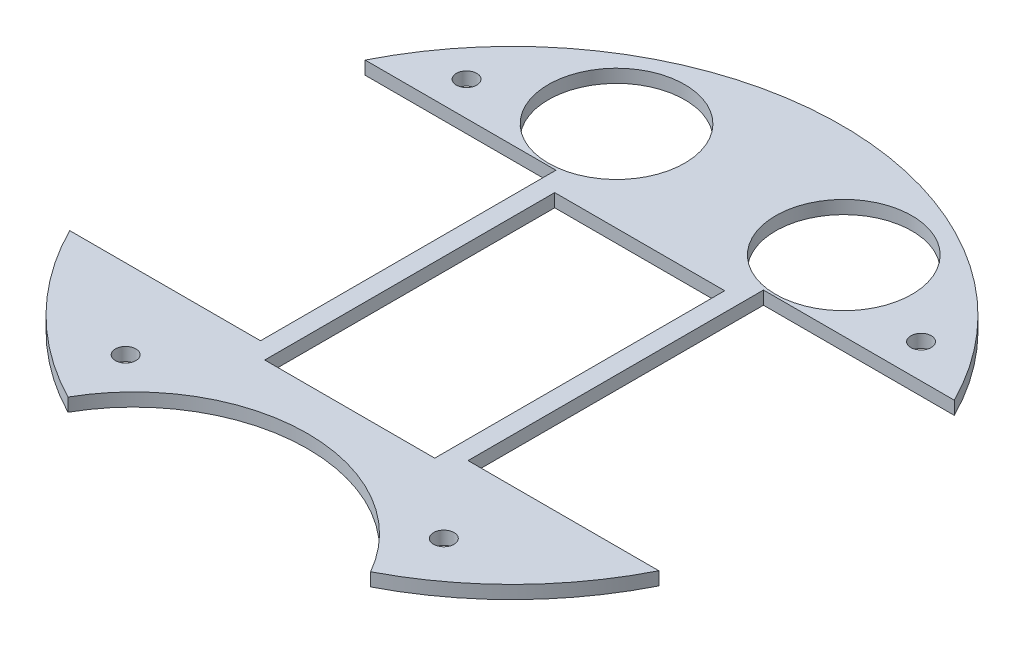
SolidWorks part; units mm, degrees
material "Acrylic (Medium-high impact)"
ref_plane "Front Plane" through (0, 0, 0) normal (0, 0, 1) x (1, 0, 0)
ref_plane "Top Plane" through (0, 0, 0) normal (0, 1, 0) x (1, 0, 0)
ref_plane "Right Plane" through (0, 0, 0) normal (1, 0, 0) x (0, 0, -1)
sketch "Sketch1" plane through (0, 0, 0) normal (0, 1, 0) x (1, 0, 0)
  line L0 (0, -83.2398) -> (-33.2911, -64.4046) construction
  line L1 (0, -83.2398) -> (0, 0) construction
  arc A0 (33.2911, -64.4046) -> (-33.2911, -64.4046) centre (0, 0) ccw
  arc A1 (33.2911, -64.4046) -> (-33.2911, -64.4046) centre (0, -83.2398) ccw
  dimension "D1" = 145
  dimension "D2" = 76.5
  dimension "D3" = 60.5
extrude "Boss-Extrude1" add sketch "Sketch1" along normal blind 2.9
sketch "solenoid placement" plane through (0, 2.9, 0) normal (0, 1, 0) x (1, 0, 0)
  line L0 (0, 0) -> (0, -36) construction
  line L1 (0, -36) -> (0, -44.9898) construction
  line L2 (-19, -36) -> (19, -36) construction
  line L3 (-19, -36) -> (-19, 28.4) construction
  line L4 (-19, 28.4) -> (19, 28.4) construction
  line L5 (19, -36) -> (19, 28.4) construction
  line L6 (-18.7, 28.1) -> (18.7, 28.1)
  line L7 (18.7, -35.7) -> (18.7, 28.1)
  line L8 (-18.7, -35.7) -> (18.7, -35.7)
  line L9 (-18.7, -35.7) -> (-18.7, 28.1)
  circle A1 centre (0, 0) radius 72.5 construction
  arc A2 (33.2911, -64.4046) -> (-33.2911, -64.4046) centre (0, 0) ccw construction
  arc A3 (33.2911, -64.4046) -> (-33.2911, -64.4046) centre (0, -83.2398) ccw construction
  dimension "D1" = 64.4
  dimension "D2" = 36
  dimension "D3" = 0.3
  dimension "D4" = 38
extrude "Cut-Extrude1" cut sketch "solenoid placement" against normal through all
sketch "Sketch3" plane through (0, 2.9, 0) normal (0, 1, 0) x (1, 0, 0)
  line L1 (-34.63, -32.5) -> (-22.83, -32.5)
  line L2 (-64.8074, -32.5) -> (-34.63, -32.5)
  line L3 (-64.8074, 32.5) -> (-22.83, 32.5)
  line L4 (-22.83, -32.5) -> (-22.83, 32.5)
  line L8 (0, 0) -> (0, 72.5) construction
  line L9 (22.83, -32.5) -> (22.83, 32.5)
  line L10 (64.8074, 32.5) -> (22.83, 32.5)
  line L11 (64.8074, -32.5) -> (34.63, -32.5)
  line L12 (34.63, -32.5) -> (22.83, -32.5)
  arc A0 (33.2911, -64.4046) -> (-33.2911, -64.4046) centre (0, 0) ccw construction
  arc A1 (64.8074, 32.5) -> (64.8074, -32.5) centre (0, 0) cw
  arc A3 (-64.8074, 32.5) -> (-64.8074, -32.5) centre (0, 0) ccw
  point P31 (-34.63, -32.5)
extrude "Cut-Extrude3" cut sketch "Sketch3" against normal through all
sketch "Sketch7" plane through (0, 2.9, 0) normal (0, 1, 0) x (1, 0, 0)
  circle A3 centre (25, 48) radius 15
  circle A4 centre (25, 48) radius 15
  circle A5 centre (-25, 48) radius 15
  circle A6 centre (-25, 48) radius 15
  dimension "D1" = 0
  dimension "D2" = 0
extrude "Cut-Extrude6" cut sketch "Sketch7" against normal through all
sketch "Sketch8" plane through (0, 2.9, 0) normal (0, 1, 0) x (1, 0, 0)
  circle A1 centre (35, -50) radius 2.25
  circle A2 centre (35, -50) radius 2.25
  circle A3 centre (-35, -50) radius 2.25
  circle A4 centre (-35, -50) radius 2.25
  circle A5 centre (-50, 40) radius 2.25
  circle A6 centre (-50, 40) radius 2.25
  circle A7 centre (50, 40) radius 2.25
  circle A8 centre (50, 40) radius 2.25
  dimension "D1" = 0
  dimension "D2" = 0
  dimension "D3" = 0
  dimension "D4" = 0
extrude "Cut-Extrude7" cut sketch "Sketch8" against normal through all
equation "\"smallPulleyTeeth\"= 15"
equation "\"largePulleyTeeth\"= 30"
equation "\"eighthThick\"= 2.9mm"
equation "\"sixteenthThick\"= 1.7mm"
equation "\"quarterThick\"=5.9mm"
equation "\"OD\"= 145mm"
equation "\"puckAngle\"= 60.5deg"
equation "\"D1@Sketch1\"=\"OD\""
equation "\"puckDiam\"= 76.5mm"
equation "\"D2@Sketch1\"=\"puckDiam\""
equation "\"D3@Sketch1\"=\"puckAngle\""
equation "\"D1@Boss-Extrude1\"=\"eighthThick\""
equation "\"axlePress\"= 5.9mm"
equation "\"press\"= 0.2mm"
equation "\"wheelClear\"= 0.3mm"
equation "\"10-32clear\"= 4.5mm"
equation "\"6-32clear\"= 3.3mm"
equation "\"8-32clear\"= 4.0mm"
equation "\"4-40clear\"= 2.55mm"
equation "\"wheelHeight\"= 22mm"
equation "\"wheelWell\"= 65mm"
